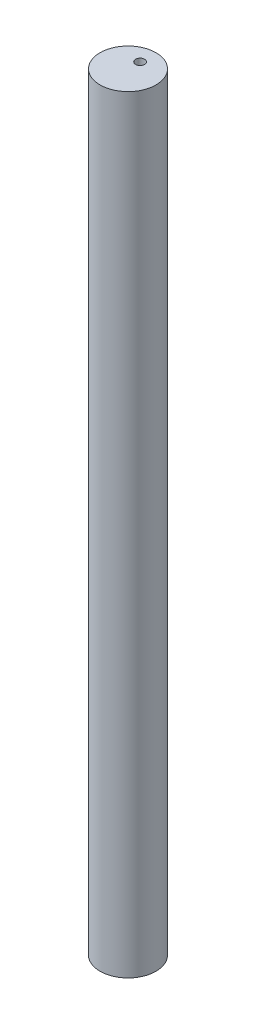
SolidWorks part; units mm, degrees
material "Brass"
ref_plane "Front Plane" through (0, 0, 0) normal (0, 0, 1) x (1, 0, 0)
ref_plane "Top Plane" through (0, 0, 0) normal (0, 1, 0) x (1, 0, 0)
ref_plane "Right Plane" through (0, 0, 0) normal (1, 0, 0) x (0, 0, -1)
sketch "Sketch2" plane through (0, 0, 0) normal (0, 1, 0) x (1, 0, 0)
  circle A0 centre (0, 0) radius 11.1
  dimension "D1" = 22.2
extrude "Boss-Extrude1" add sketch "Sketch2" along normal blind 304.8
sketch "Sketch3" plane through (0, 304.8, 0) normal (0, 1, 0) x (1, 0, 0)
  line L0 (0, 11.1) -> (0, 6.6) construction
  line L1 (0, 6.6) -> (0, 4.8) construction
  circle A0 centre (0, 0) radius 11.1 construction
  circle A1 centre (0, 4.8) radius 1.8
  dimension "D1" = 4.5
  dimension "D2" = 1.8
extrude "Cut-Extrude1" cut sketch "Sketch3" against normal blind 12.6
